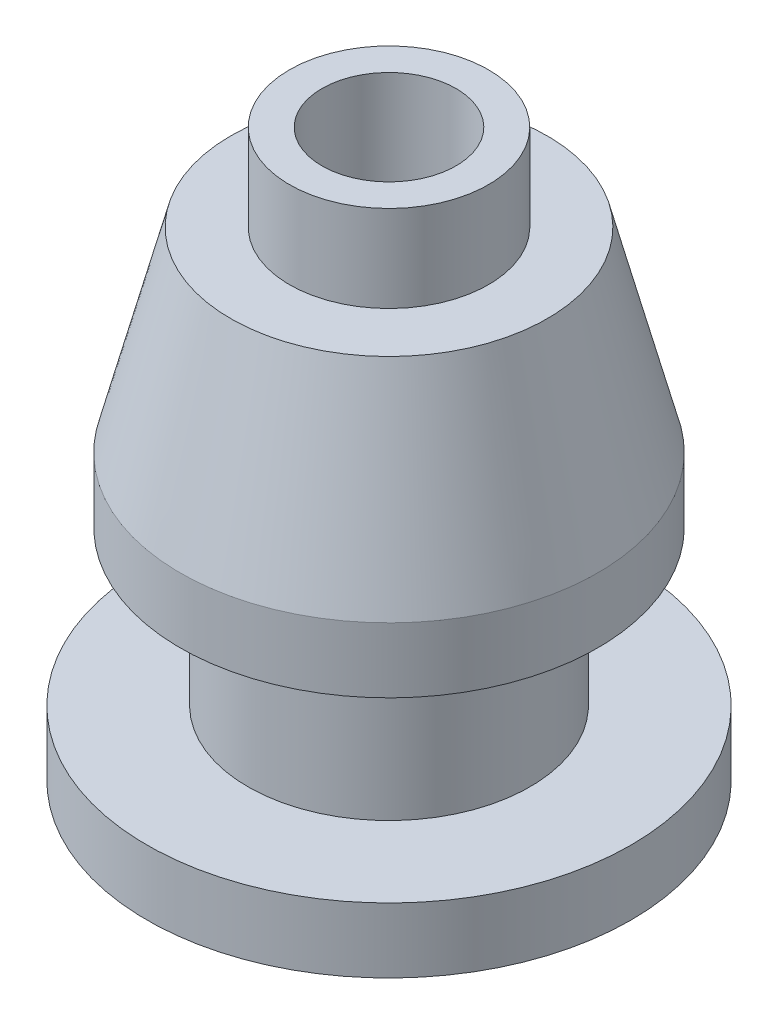
SolidWorks part; units mm, degrees
ref_plane "Front Plane" through (0, 0, 0) normal (0, 0, 1) x (1, 0, 0)
ref_plane "Top Plane" through (0, 0, 0) normal (0, 1, 0) x (1, 0, 0)
ref_plane "Right Plane" through (0, 0, 0) normal (1, 0, 0) x (0, 0, -1)
sketch "Sketch1" plane through (0, 0, 0) normal (0, 0, 1) x (1, 0, 0)
  line L0 (30.9574, 237.5307) -> (30.9574, -23.6395)
  line L1 (-43.4043, -23.6395) -> (-134992.3254, -23.6395) construction
  line L2 (0, 2.5532) -> (0, -134946.368) construction
  line L3 (30.9574, -23.6395) -> (111.7021, -23.6395)
  line L4 (111.7021, -23.6395) -> (111.7021, 6.3605)
  line L5 (111.7021, 6.3605) -> (65.1064, 6.3605)
  line L6 (65.1064, 6.3605) -> (65.1064, 77.5307)
  line L7 (65.1064, 77.5307) -> (96.383, 77.5307)
  line L9 (73.0851, 197.5307) -> (45.9574, 197.5307)
  line L10 (45.9574, 197.5307) -> (45.9574, 237.5307)
  line L11 (45.9574, 237.5307) -> (30.9574, 237.5307)
  line L12 (96.383, 77.5307) -> (96.383, 107.5307)
  line L13 (96.383, 107.5307) -> (73.0851, 197.5307)
  dimension "D1" = 30
  dimension "D2" = 71.1702
  dimension "D3" = 30
  dimension "D4" = 90
  dimension "D5" = 40
  dimension "D6" = 15
revolve "Revolve1" add sketch "Sketch1" angle 360 about L2
